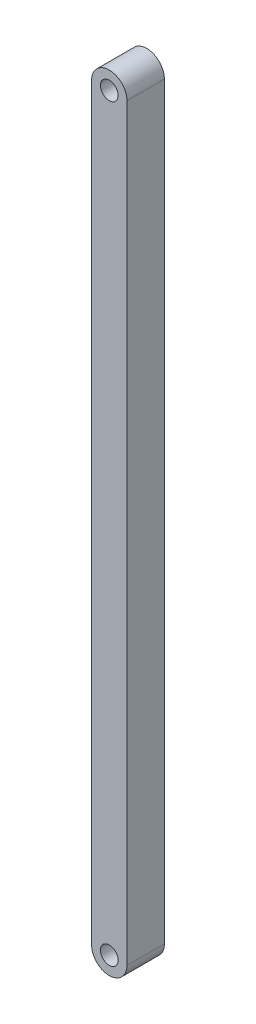
SolidWorks part; units mm, degrees
material "5052-H32"
ref_plane "Front Plane" through (0, 0, 0) normal (0, 0, 1) x (1, 0, 0)
ref_plane "Top Plane" through (0, 0, 0) normal (0, 1, 0) x (1, 0, 0)
ref_plane "Right Plane" through (0, 0, 0) normal (1, 0, 0) x (0, 0, -1)
sketch "Sketch1" plane through (0, 0, 0) normal (0, 0, 1) x (1, 0, 0)
  line L0 (-6, -254) -> (-6, 0)
  line L1 (6, 0) -> (6, -254)
  arc A0 (6, 0) -> (-6, 0) centre (0, 0) ccw
  arc A1 (-6, -254) -> (6, -254) centre (0, -254) ccw
  circle A2 centre (0, 0) radius 3
  circle A3 centre (0, -254) radius 3
  dimension "D1" = 6
  dimension "D3" = 6
  dimension "D4" = 6
  dimension "D2" = 254
extrude "Boss-Extrude1" add sketch "Sketch1" along normal blind 12.7
sketch "Sketch2" plane through (0, 0, 0) normal (0, 0, -1) x (-1, 0, 0)
  line L0 (-605.189, 2050.457) -> (-44.5223, 2050.457) construction
